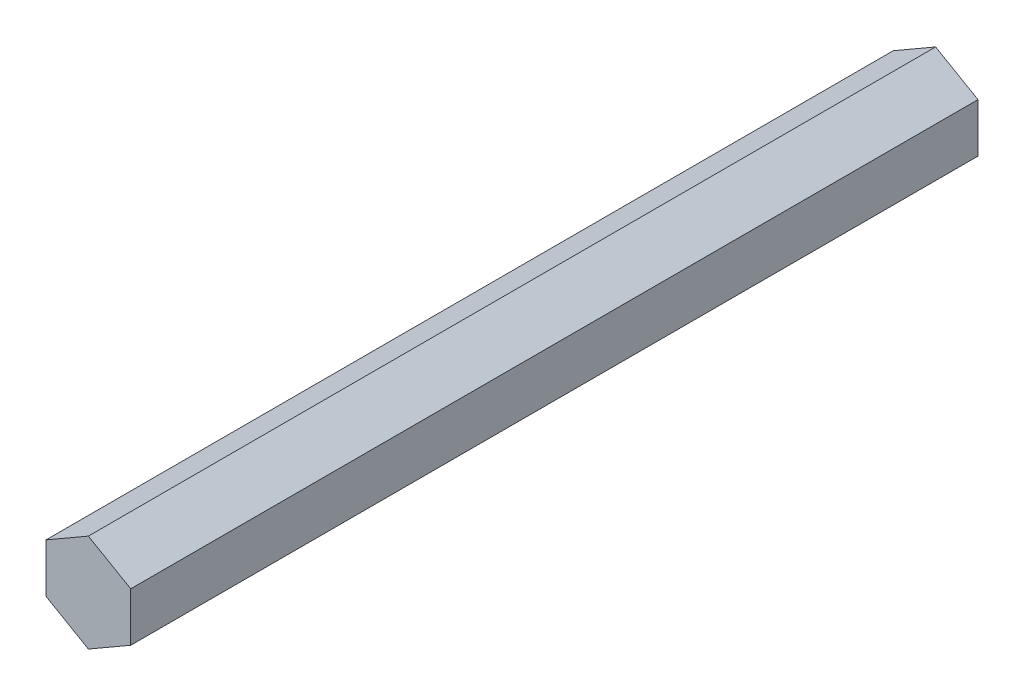
SolidWorks part; units mm, degrees
material "6061-T6 (SS)"
ref_plane "Front Plane" through (0, 0, 0) normal (0, 0, 1) x (1, 0, 0)
ref_plane "Top Plane" through (0, 0, 0) normal (0, 1, 0) x (1, 0, 0)
ref_plane "Right Plane" through (0, 0, 0) normal (1, 0, 0) x (0, 0, -1)
sketch "Sketch2" plane through (0, 0, 0) normal (0, 0, 1) x (1, 0, 0)
  line L1 (0, -7.3323) -> (6.35, -3.6662)
  line L2 (6.35, -3.6662) -> (6.35, 3.6662)
  line L3 (6.35, 3.6662) -> (0, 7.3323)
  line L4 (0, 7.3323) -> (-6.35, 3.6662)
  line L5 (-6.35, 3.6662) -> (-6.35, -3.6662)
  line L6 (-6.35, -3.6662) -> (0, -7.3323)
  circle A0 centre (0, 0) radius 6.35 construction
  dimension "D1" = 12.7
extrude "Boss-Extrude1" add sketch "Sketch2" along normal blind 127
